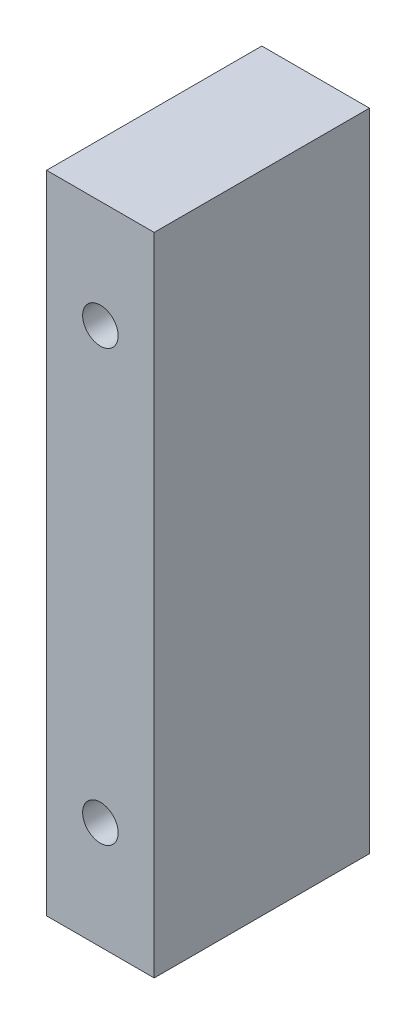
SolidWorks part; units mm, degrees
ref_plane "前视基准面" through (0, 0, 0) normal (0, 0, 1) x (1, 0, 0)
ref_plane "上视基准面" through (0, 0, 0) normal (0, 1, 0) x (1, 0, 0)
ref_plane "右视基准面" through (0, 0, 0) normal (1, 0, 0) x (0, 0, -1)
other "Configuration Table"
sketch "草图1" plane through (0, 0, 0) normal (0, 0, 1) x (1, 0, 0)
  line L1 (0, 0) -> (20, 0)
  line L2 (0, 0) -> (0, 120)
  line L3 (0, 120) -> (20, 120)
  line L4 (20, 0) -> (20, 120)
  circle A0 centre (10, 20) radius 3.3
  circle A1 centre (10, 100) radius 3.3
extrude "Fixed_jaw_20x120x40" add sketch "草图1" along normal blind 40
